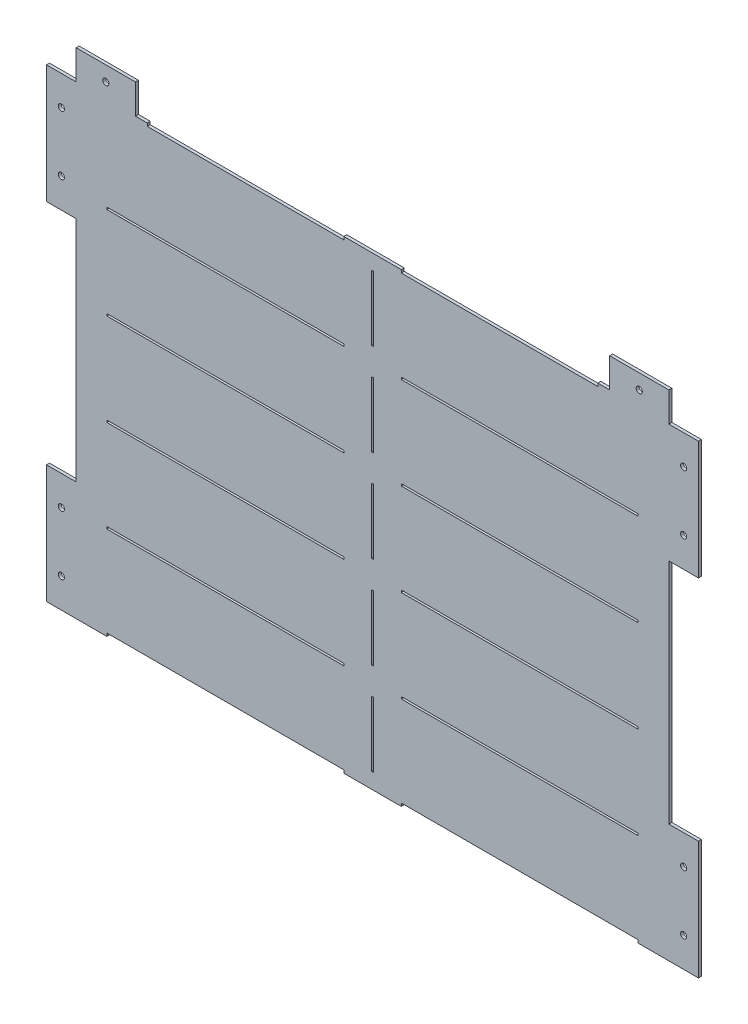
SolidWorks part; units mm, degrees
material "6061-T6 (SS)"
ref_plane "X-Y Datum" through (0, 0, 0) normal (0, 0, 1) x (1, 0, 0)
ref_plane "X-Z Datum" through (0, 0, 0) normal (0, 1, 0) x (1, 0, 0)
ref_plane "Y-Z Datum" through (0, 0, 0) normal (1, 0, 0) x (0, 0, -1)
sketch "Master Sketch" plane through (0, 0, 0) normal (0, 0, 1) x (1, 0, 0)
  line L0 (1.143, 50.5714) -> (314.5028, 50.5714) construction
  line L1 (-317.6778, 249.174) -> (317.6778, 249.174)
  line L2 (-317.6778, 249.174) -> (-317.6778, -249.174)
  line L3 (-317.6778, -249.174) -> (317.6778, -249.174)
  line L4 (317.6778, 249.174) -> (317.6778, -249.174)
  line L5 (-317.6778, 249.174) -> (317.6778, -249.174) construction
  line L6 (-317.6778, -249.174) -> (317.6778, 249.174) construction
  line L7 (-1.143, 249.174) -> (1.143, 249.174) construction
  line L8 (-1.143, 249.174) -> (-1.143, -249.174) construction
  line L9 (-1.143, -249.174) -> (1.143, -249.174) construction
  line L10 (1.143, 249.174) -> (1.143, -249.174) construction
  line L11 (-1.143, 249.174) -> (1.143, -249.174) construction
  line L12 (-1.143, -249.174) -> (1.143, 249.174) construction
  line L13 (1.143, 245.999) -> (314.5028, 245.999) construction
  line L14 (1.143, 245.999) -> (1.143, 149.4282) construction
  line L15 (1.143, 149.4282) -> (314.5028, 149.4282) construction
  line L16 (314.5028, 245.999) -> (314.5028, 149.4282) construction
  line L17 (1.143, 245.999) -> (314.5028, 149.4282) construction
  line L18 (1.143, 149.4282) -> (314.5028, 245.999) construction
  line L19 (1.143, 147.1422) -> (314.5028, 147.1422) construction
  line L20 (314.5028, 147.1422) -> (314.5028, 50.5714) construction
  line L21 (1.143, 147.1422) -> (1.143, 50.5714) construction
  line L22 (1.143, -48.2854) -> (314.5028, -48.2854) construction
  line L23 (1.143, 48.2854) -> (314.5028, 48.2854) construction
  line L24 (314.5028, 48.2854) -> (314.5028, -48.2854) construction
  line L25 (1.143, 48.2854) -> (1.143, -48.2854) construction
  line L26 (1.143, -147.1422) -> (314.5028, -147.1422) construction
  line L27 (1.143, -50.5714) -> (314.5028, -50.5714) construction
  line L28 (314.5028, -50.5714) -> (314.5028, -147.1422) construction
  line L29 (1.143, -50.5714) -> (1.143, -147.1422) construction
  line L30 (1.143, -245.999) -> (314.5028, -245.999) construction
  line L31 (1.143, -149.4282) -> (314.5028, -149.4282) construction
  line L32 (314.5028, -149.4282) -> (314.5028, -245.999) construction
  line L33 (1.143, -149.4282) -> (1.143, -245.999) construction
  line L34 (0, 249.174) -> (0, -249.174) construction
  line L35 (-1.143, -149.4282) -> (-1.143, -245.999) construction
  line L36 (-314.5028, -149.4282) -> (-314.5028, -245.999) construction
  line L37 (-1.143, -149.4282) -> (-314.5028, -149.4282) construction
  line L38 (-1.143, -245.999) -> (-314.5028, -245.999) construction
  line L39 (-1.143, -50.5714) -> (-1.143, -147.1422) construction
  line L40 (-314.5028, -50.5714) -> (-314.5028, -147.1422) construction
  line L41 (-1.143, -50.5714) -> (-314.5028, -50.5714) construction
  line L42 (-1.143, -147.1422) -> (-314.5028, -147.1422) construction
  line L43 (-1.143, 48.2854) -> (-1.143, -48.2854) construction
  line L44 (-314.5028, 48.2854) -> (-314.5028, -48.2854) construction
  line L45 (-1.143, 48.2854) -> (-314.5028, 48.2854) construction
  line L46 (-1.143, -48.2854) -> (-314.5028, -48.2854) construction
  line L47 (-1.143, 147.1422) -> (-1.143, 50.5714) construction
  line L48 (-314.5028, 147.1422) -> (-314.5028, 50.5714) construction
  line L49 (-1.143, 147.1422) -> (-314.5028, 147.1422) construction
  line L50 (-1.143, 149.4282) -> (-314.5028, 245.999) construction
  line L51 (-1.143, 245.999) -> (-314.5028, 149.4282) construction
  line L52 (-314.5028, 245.999) -> (-314.5028, 149.4282) construction
  line L53 (-1.143, 149.4282) -> (-314.5028, 149.4282) construction
  line L54 (-1.143, 245.999) -> (-1.143, 149.4282) construction
  line L55 (-1.143, 245.999) -> (-314.5028, 245.999) construction
  line L56 (-1.143, 249.174) -> (-1.143, -249.174) construction
  line L57 (-1.143, 50.5714) -> (-314.5028, 50.5714) construction
  line L59 (2.413, -152.8699) -> (313.2328, -152.8699) construction
  line L60 (2.413, -152.8699) -> (2.413, -242.5573) construction
  line L61 (2.413, -242.5573) -> (313.2328, -242.5573) construction
  line L62 (313.2328, -152.8699) -> (313.2328, -242.5573) construction
  line L63 (2.413, -152.8699) -> (313.2328, -242.5573) construction
  line L64 (2.413, -242.5573) -> (313.2328, -152.8699) construction
  point P0 (0, 0)
  point P6 (0, 0)
  point P11 (157.8229, 197.7136)
  point P54 (-157.8229, 197.7136)
  point P55 (157.8229, -197.7136)
  point P60 (157.8229, -149.4282)
  point P61 (314.5028, -197.7136)
  point P62 (-314.5028, 98.8568)
  point P63 (-314.5028, 0)
  dimension "D1" = 3.175
  dimension "D2" = 498.348
  dimension "D3" = 2.286
  dimension "D4" = 313.3598
  dimension "D5" = 96.5708
  dimension "D6" = 3.175
  dimension "D7" = 5
  dimension "D8" = 2.286
  dimension "D9" = 89.6874
  dimension "D10" = 310.8198
  dimension "D11" = 98.8568
  dimension "D12" = 635.3556
extrude "Boss-Extrude1" add sketch "Master Sketch" along normal blind 3.175
sketch "Sketch2" plane through (0, 0, 3.175) normal (0, 0, 1) x (1, 0, 0)
  line L0 (0, 317.2302) -> (0, -317.2302) construction
  line L1 (-349.4278, -185.674) -> (-317.6778, -185.674) construction
  line L6 (-333.5528, -122.174) -> (-333.5528, -185.674) construction
  line L7 (-380.7135, 0) -> (380.7135, 0) construction
  line L8 (-333.5528, -185.674) -> (-333.5528, -153.924) construction
  line L9 (-333.5528, -122.174) -> (-333.5528, -249.174) construction
  line L10 (-317.6778, -249.174) -> (-349.4278, -249.174)
  line L11 (-317.6778, -249.174) -> (-317.6778, -122.174)
  line L12 (-317.6778, -122.174) -> (-349.4278, -122.174)
  line L13 (-349.4278, -249.174) -> (-349.4278, -122.174)
  line L14 (-333.5528, -153.924) -> (-340.9316, -153.924) construction
  circle A6 centre (-333.5528, -153.924) radius 3 construction
  circle A8 centre (-333.5528, -217.424) radius 3 construction
  point P4 (0, 0)
  point P18 (0, 0)
  dimension "D8" = 31.75
  dimension "D1" = 6
  dimension "D9" = 127
extrude "Boss-Extrude2" add sketch "Sketch2" against normal blind 3.175
hole_wizard "M6 Clearance Hole1" positions "Sketch3" profile "Sketch4" hole size "M6" standard "ANSI Metric" end condition through all
sketch "Sketch3" plane through (0, 0, 3.175) normal (0, 0, 1) x (1, 0, 0)
  point P47 (-333.5528, -217.424)
  point P50 (-333.5528, -153.924)
sketch "Sketch4" plane through (-333.5528, -217.424, 3.175) normal (1, 0, 0) x (0, -1, 0)
  line L0 (0, 0) -> (0, 3.175)
  line L1 (0, 3.175) -> (3.3, 3.175)
  line L2 (3.3, 3.175) -> (3.3, 0)
  line L5 (3.3, 0) -> (0, 0)
  line L11 (0, -6.35) -> (0, 107.95) construction
  dimension "Thru Hole Dia." = 6.6
  dimension "Thru Hole Depth" = 3.175
mirror "Mirror1" about plane through (0, 0, 0) normal (1, 0, 0) of "Boss-Extrude2", "M6 Clearance Hole1"
mirror "Mirror7" about plane through (0, 0, 0) normal (0, 1, 0) of "Mirror1", "Boss-Extrude2", "M6 Clearance Hole1"
sketch "Sketch5" plane through (0, 0, 3.175) normal (0, 0, 1) x (1, 0, 0)
  line L5 (-1.143, 232.6386) -> (1.143, 232.6386)
  line L6 (-1.143, 232.6386) -> (-1.143, 162.7886)
  line L7 (-1.143, 162.7886) -> (1.143, 162.7886)
  line L8 (1.143, 232.6386) -> (1.143, 162.7886)
  line L9 (-157.8229, 197.7136) -> (157.8229, 197.7136) construction
  line L10 (-1.143, 232.6386) -> (1.143, 162.7886) construction
  line L11 (-1.143, 162.7886) -> (1.143, 232.6386) construction
  point P0 (0, 0)
  point P1 (0, 197.7136)
  dimension "D1" = 2.286
  dimension "D2" = 69.85
extrude "Cut-Extrude1" cut sketch "Sketch5" against normal through all
pattern_linear "LPattern1" count 5 spacing 98.8568 along (0, -1, 0) of "Cut-Extrude1"
sketch "Sketch7" plane through (0, 0, 3.175) normal (0, 0, 1) x (1, 0, 0)
  line L0 (-157.8229, 149.4282) -> (-157.8229, 147.1422) construction
  line L1 (-1.143, 149.4282) -> (-314.5028, 149.4282) construction
  line L2 (-1.143, 147.1422) -> (-314.5028, 147.1422) construction
  line L3 (-157.8229, 50.5714) -> (-157.8229, 48.2854) construction
  line L4 (-284.8229, 149.4282) -> (-30.8229, 149.4282)
  line L5 (-284.8229, 149.4282) -> (-284.8229, 147.1422)
  line L6 (-284.8229, 147.1422) -> (-30.8229, 147.1422)
  line L7 (-30.8229, 149.4282) -> (-30.8229, 147.1422)
  line L8 (-284.8229, 149.4282) -> (-30.8229, 147.1422) construction
  line L9 (-284.8229, 147.1422) -> (-30.8229, 149.4282) construction
  line L10 (-1.143, 50.5714) -> (-314.5028, 50.5714) construction
  line L11 (-1.143, 48.2854) -> (-314.5028, 48.2854) construction
  point P6 (-157.8229, 148.2852)
  dimension "D1" = 2.286
  dimension "D2" = 254
extrude "Cut-Extrude3" cut sketch "Sketch7" against normal through all
pattern_linear "LPattern2" count 4 spacing 98.8568 along (0, -1, 0) of "Cut-Extrude3"
mirror "Mirror4" about plane through (0, 0, 0) normal (1, 0, 0) of "LPattern2", "Cut-Extrude3"
sketch "Sketch10" plane through (0, 0, 3.175) normal (0, 0, 1) x (1, 0, 0)
  line L0 (-317.6778, 122.174) -> (-317.6778, 249.174) construction
  line L5 (349.4278, 249.174) -> (-349.4278, 249.174) construction
  line L6 (-317.6778, 265.049) -> (-254.1778, 265.049) construction
  line L9 (-317.6778, 249.174) -> (-254.1778, 249.174)
  line L10 (-317.6778, 249.174) -> (-317.6778, 280.924)
  line L11 (-317.6778, 280.924) -> (-254.1778, 280.924)
  line L12 (-254.1778, 249.174) -> (-254.1778, 280.924)
  circle A4 centre (-285.9278, 265.049) radius 3
  dimension "D1" = 6
  dimension "D4" = 31.75
  dimension "D5" = 63.5
extrude "Boss-Extrude3" add sketch "Sketch10" against normal blind 3.175
hole_wizard "M6 Clearance Hole2" positions "Sketch11" profile "Sketch12" hole size "M6" standard "ANSI Metric" end condition through all
sketch "Sketch11" plane through (0, 0, 3.175) normal (0, 0, 1) x (1, 0, 0)
  point P16 (-285.9278, 265.049)
sketch "Sketch12" plane through (-285.9278, 265.049, 3.175) normal (1, 0, 0) x (0, -1, 0)
  line L0 (0, 0) -> (0, 3.175)
  line L1 (0, 3.175) -> (3.3, 3.175)
  line L2 (3.3, 3.175) -> (3.3, 0)
  line L5 (3.3, 0) -> (0, 0)
  line L11 (0, -6.35) -> (0, 107.95) construction
  dimension "Thru Hole Dia." = 6.6
  dimension "Thru Hole Depth" = 3.175
mirror "Mirror6" about plane through (0, 0, 0) normal (1, 0, 0) of "M6 Clearance Hole2", "Boss-Extrude3"
sketch "Sketch6" plane through (0, 0, 3.175) normal (0, 0, 1) x (1, 0, 0)
  line L0 (-157.8229, 245.999) -> (-157.8229, 249.174) construction
  line L1 (-1.143, 245.999) -> (-314.5028, 245.999) construction
  line L2 (-317.6778, 249.174) -> (317.6778, 249.174) construction
  line L3 (0, -78.309) -> (0, 78.309) construction
  line L4 (-284.8229, 249.174) -> (-30.8229, 249.174)
  line L5 (-284.8229, 249.174) -> (-284.8229, 245.999)
  line L6 (-284.8229, 245.999) -> (-30.8229, 245.999)
  line L7 (-30.8229, 249.174) -> (-30.8229, 245.999)
  line L8 (-284.8229, 249.174) -> (-30.8229, 245.999) construction
  line L9 (-284.8229, 245.999) -> (-30.8229, 249.174) construction
  line L10 (30.8229, 249.174) -> (30.8229, 245.999)
  line L11 (284.8229, 249.174) -> (30.8229, 249.174)
  line L12 (284.8229, 245.999) -> (30.8229, 245.999)
  line L13 (284.8229, 249.174) -> (284.8229, 245.999)
  line L14 (1.7463, 0) -> (-1.7463, 0) construction
  line L15 (-284.8229, -245.999) -> (-30.8229, -249.174) construction
  line L16 (-284.8229, -249.174) -> (-30.8229, -245.999) construction
  line L17 (-157.8229, -245.999) -> (-157.8229, -249.174) construction
  line L18 (284.8229, -249.174) -> (284.8229, -245.999)
  line L19 (284.8229, -245.999) -> (30.8229, -245.999)
  line L20 (284.8229, -249.174) -> (30.8229, -249.174)
  line L21 (30.8229, -249.174) -> (30.8229, -245.999)
  line L22 (-30.8229, -249.174) -> (-30.8229, -245.999)
  line L23 (-284.8229, -245.999) -> (-30.8229, -245.999)
  line L24 (-284.8229, -249.174) -> (-284.8229, -245.999)
  line L25 (-284.8229, -249.174) -> (-30.8229, -249.174)
  line L26 (-241.4778, 245.999) -> (-241.4778, 249.174)
  line L27 (-254.1778, 249.174) -> (-254.1778, 280.924) construction
  line L28 (241.4778, 245.999) -> (241.4778, 249.174)
  point P6 (-157.8229, 247.5865)
  point P29 (-157.8229, -247.5865)
  dimension "D1" = 3.175
  dimension "D2" = 254
  dimension "D3" = 12.7
extrude "Cut-Extrude2" cut sketch "Sketch6" against normal through all
